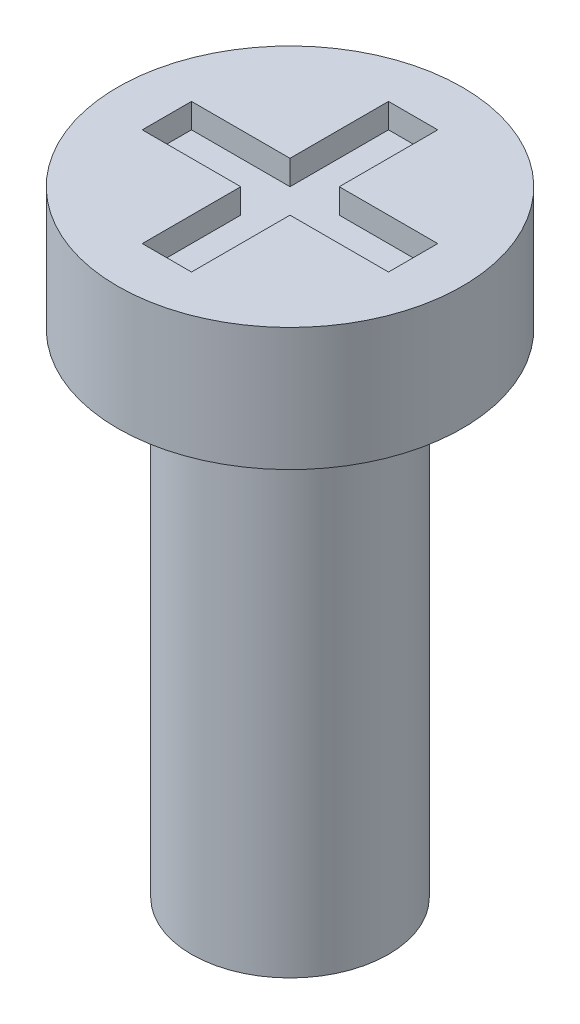
SolidWorks part; units mm, degrees
material "Plain Carbon Steel"
ref_plane "Front Plane" through (0, 0, 0) normal (0, 0, 1) x (1, 0, 0)
ref_plane "Top Plane" through (0, 0, 0) normal (0, 1, 0) x (1, 0, 0)
ref_plane "Right Plane" through (0, 0, 0) normal (1, 0, 0) x (0, 0, -1)
sketch "Sketch1" plane through (0, 0, 0) normal (0, 1, 0) x (1, 0, 0)
  circle A0 centre (0, 0) radius 0.4
extrude "Boss-Extrude1" add sketch "Sketch1" along normal blind 2
sketch "Sketch2" plane through (0, 2, 0) normal (0, 1, 0) x (1, 0, 0)
  circle A0 centre (0, 0) radius 0.7
extrude "Boss-Extrude2" add sketch "Sketch2" along normal blind 0.5
sketch "Sketch3" plane through (0, 2.5, 0) normal (0, 1, 0) x (1, 0, 0)
  line L0 (-0.1, -0.1) -> (-0.1, -0.5)
  line L1 (-0.5, 0.1) -> (-0.1, 0.1)
  line L2 (-0.5, 0.1) -> (-0.5, -0.1)
  line L3 (-0.5, -0.1) -> (-0.1, -0.1)
  line L4 (0.5, 0.1) -> (0.5, -0.1)
  line L5 (-0.1, 0.5) -> (0.1, 0.5)
  line L6 (-0.1, 0.5) -> (-0.1, 0.1)
  line L7 (-0.1, -0.5) -> (0.1, -0.5)
  line L8 (0.1, 0.5) -> (0.1, 0.1)
  line L9 (0.1, 0.1) -> (0.5, 0.1)
  line L10 (0.1, -0.1) -> (0.1, -0.5)
  line L11 (0.1, -0.1) -> (0.5, -0.1)
  dimension "D1" = 0.1
  dimension "D2" = 0.1
  dimension "D3" = 0.5
  dimension "D4" = 0.5
  dimension "D5" = 0.1
  dimension "D6" = 0.1
  dimension "D7" = 0.5
  dimension "D8" = 0.5
extrude "Cut-Extrude1" cut sketch "Sketch3" against normal blind 0.1
